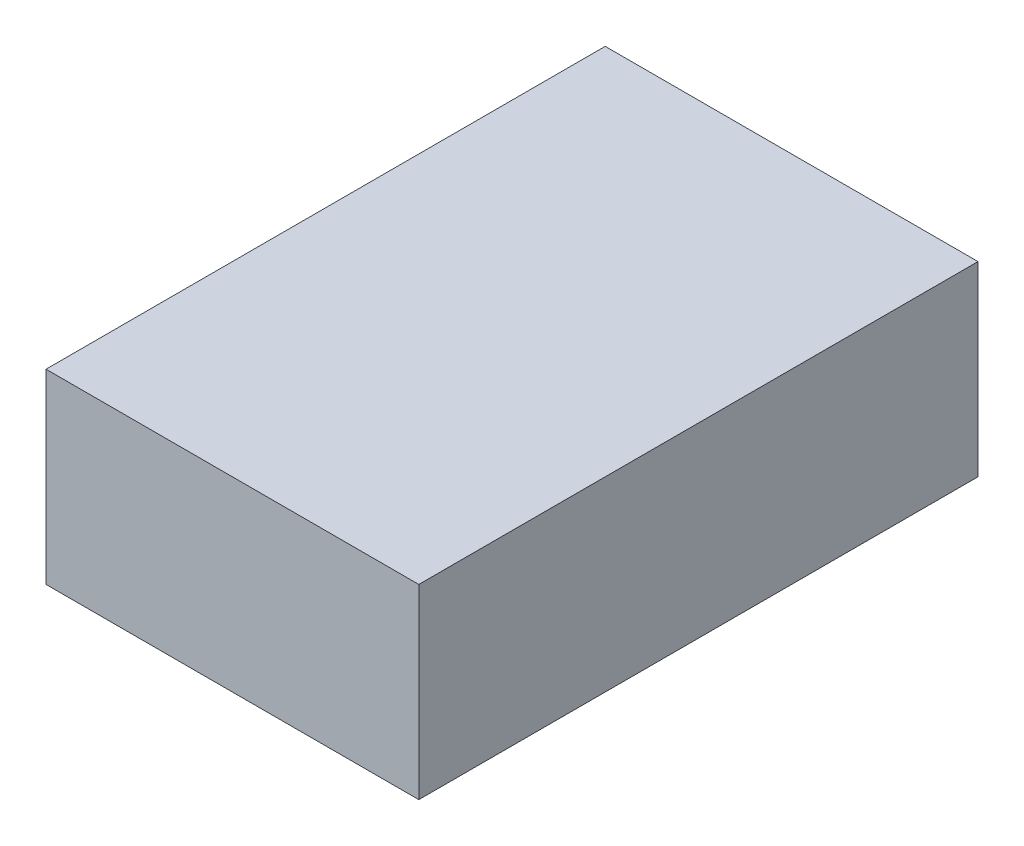
SolidWorks part; units mm, degrees
material "Rubber"
ref_plane "Front Plane" through (0, 0, 0) normal (0, 0, 1) x (1, 0, 0)
ref_plane "Top Plane" through (0, 0, 0) normal (0, 1, 0) x (1, 0, 0)
ref_plane "Right Plane" through (0, 0, 0) normal (1, 0, 0) x (0, 0, -1)
sketch "Sketch1" plane through (0, 0, 0) normal (0, 1, 0) x (1, 0, 0)
  line L1 (-12.4959, 25.8113) -> (38.3041, 25.8113)
  line L2 (-12.4959, 25.8113) -> (-12.4959, -50.3887)
  line L3 (-12.4959, -50.3887) -> (38.3041, -50.3887)
  line L4 (38.3041, 25.8113) -> (38.3041, -50.3887)
  dimension "D1" = 76.2
  dimension "D2" = 50.8
extrude "Boss-Extrude1" add sketch "Sketch1" along normal blind 25.4
